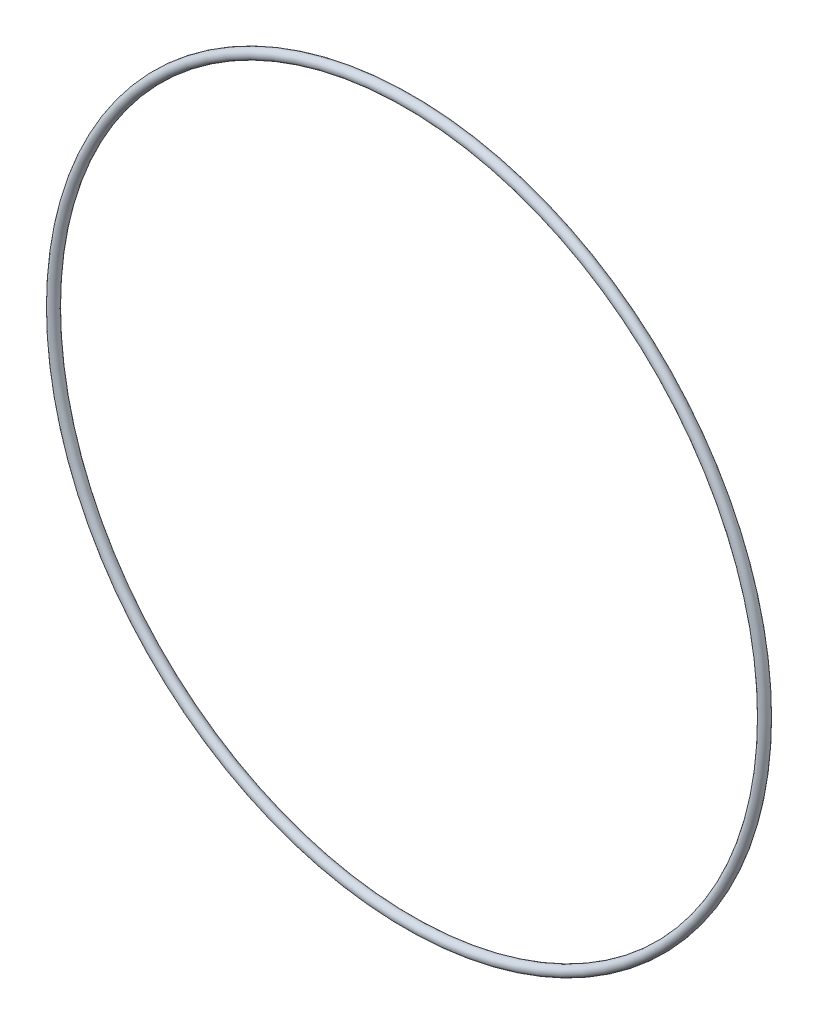
SolidWorks part; units mm, degrees
material "Copper"
ref_plane "Front Plane" through (0, 0, 0) normal (0, 0, 1) x (1, 0, 0)
ref_plane "Top Plane" through (0, 0, 0) normal (0, 1, 0) x (1, 0, 0)
ref_plane "Right Plane" through (0, 0, 0) normal (1, 0, 0) x (0, 0, -1)
sketch "Sketch1" plane through (0, 0, 0) normal (0, 0, 1) x (1, 0, 0)
  circle A0 centre (0, 0) radius 58
  dimension "D1" = 116
sweep "Sweep1" add path "Sketch1" circular profile diameter 1.6256 parameters "D3"=1.6256
